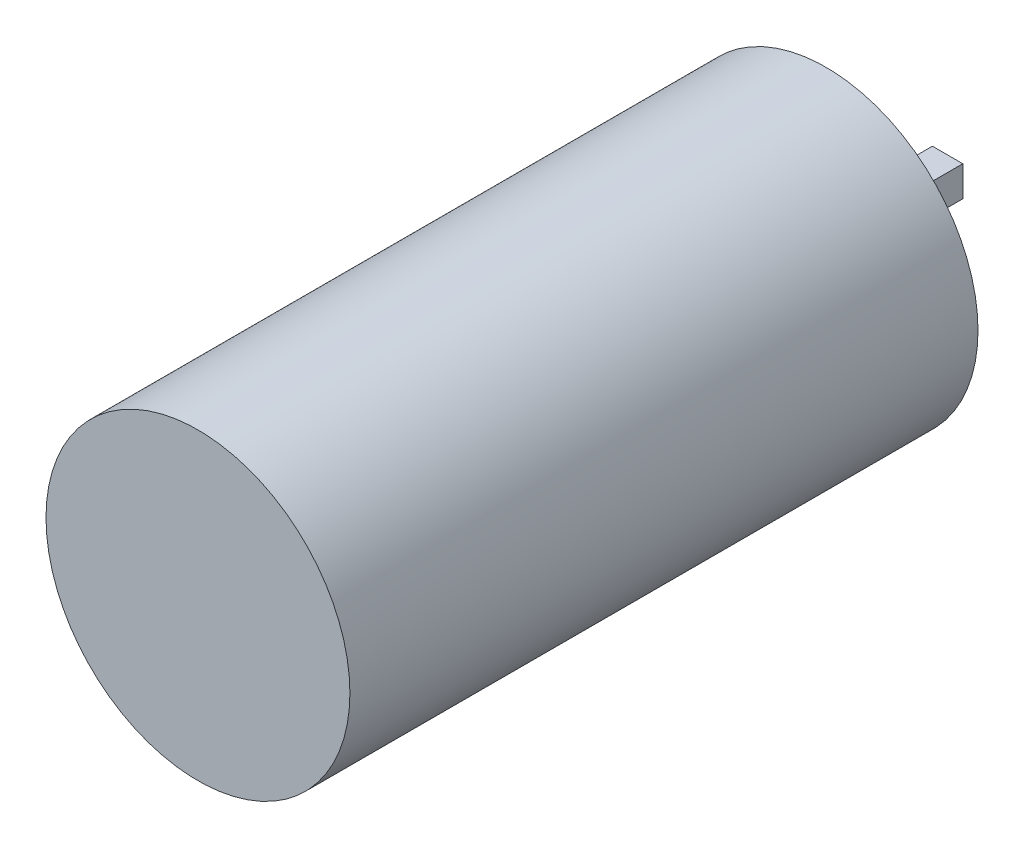
SolidWorks part; units mm, degrees
ref_plane "Plan de face" through (0, 0, 0) normal (0, 0, 1) x (1, 0, 0)
ref_plane "Plan de dessus" through (0, 0, 0) normal (0, 1, 0) x (1, 0, 0)
ref_plane "Plan de droite" through (0, 0, 0) normal (1, 0, 0) x (0, 0, -1)
sketch "Esquisse1" plane through (0, 0, 0) normal (0, 0, 1) x (1, 0, 0)
  circle A0 centre (0, 0) radius 15
extrude "Boss.-Extru.1" add sketch "Esquisse1" along normal blind 62
sketch "Esquisse2" plane through (0, 0, 0) normal (0, 0, -1) x (-1, 0, 0)
  line L1 (1.5, -1.5) -> (-1.5, -1.5)
  line L2 (1.5, -1.5) -> (1.5, 1.5)
  line L3 (1.5, 1.5) -> (-1.5, 1.5)
  line L4 (-1.5, -1.5) -> (-1.5, 1.5)
  line L5 (1.5, -1.5) -> (-1.5, 1.5) construction
  line L6 (1.5, 1.5) -> (-1.5, -1.5) construction
  point P0 (0, 0)
  dimension "D1" = 3
  dimension "D2" = 3
extrude "Boss.-Extru.2" add sketch "Esquisse2" along normal blind 12
